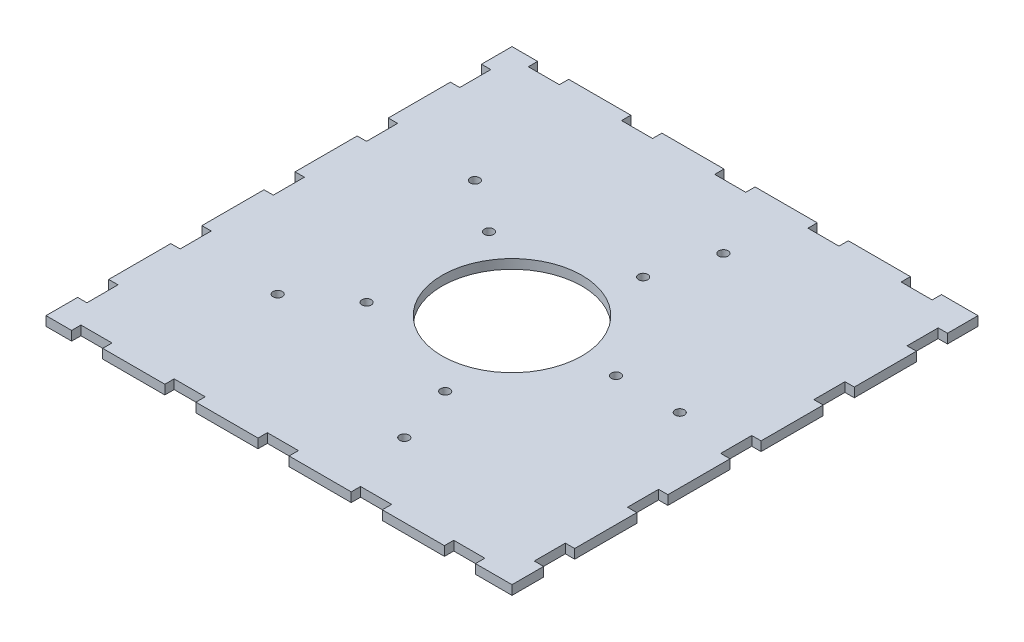
SolidWorks part; units mm, degrees
ref_plane "Front Plane" through (0, 0, 0) normal (0, 0, 1) x (1, 0, 0)
ref_plane "Top Plane" through (0, 0, 0) normal (0, 1, 0) x (1, 0, 0)
ref_plane "Right Plane" through (0, 0, 0) normal (1, 0, 0) x (0, 0, -1)
sketch "Sketch1" plane through (0, 0, 0) normal (0, 1, 0) x (-1, 0, 0)
  line L0 (75, -75) -> (-75, -75)
  line L1 (-75, -75) -> (-75, 75)
  line L2 (-75, 75) -> (75, 75)
  line L3 (75, 75) -> (75, -75)
  dimension "D1" = 150
  dimension "D2" = 150
extrude "Boss-Extrude1" add sketch "Sketch1" along normal blind 3 contours L0 L1 L2 L3
sketch "Sketch2" plane through (0, 3, 0) normal (0, 1, 0) x (1, 0, 0)
  circle A0 centre (0, 0) radius 22.5
  dimension "D1" = 45
extrude "Cut-Extrude1" cut sketch "Sketch2" against normal blind 3
sketch "Sketch3" plane through (0, 3, 0) normal (0, 1, 0) x (1, 0, 0)
  line L0 (-66.75, 75) -> (-66.75, 72)
  line L1 (-75, 75) -> (75, 75) construction
  line L2 (-66.75, 72) -> (-56.75, 72)
  line L3 (-56.75, 72) -> (-56.75, 75)
  line L4 (-56.75, 75) -> (-66.75, 75)
  line L5 (-75, 0) -> (75, 0) construction
  line L6 (-75, -75) -> (-75, 75) construction
  line L7 (75, 75) -> (75, -75) construction
  line L8 (-56.75, -75) -> (-66.75, -75)
  line L9 (-56.75, -72) -> (-56.75, -75)
  line L10 (-66.75, -72) -> (-56.75, -72)
  line L11 (-66.75, -75) -> (-66.75, -72)
  dimension "D1" = 10
  dimension "D2" = 3
extrude "Cut-Extrude2" cut sketch "Sketch3" against normal blind 3
pattern_linear "LPattern1" count 5 spacing 30 along (1, 0, 0) of "Cut-Extrude2"
sketch "Sketch4" plane through (0, 3, 0) normal (0, 1, 0) x (1, 0, 0)
  line L0 (-75, -64.8253) -> (-72, -64.8253)
  line L1 (-75, -75) -> (-75, 75) construction
  line L2 (-72, -64.8253) -> (-72, -54.8253)
  line L3 (-72, -54.8253) -> (-75, -54.8253)
  line L4 (-75, -54.8253) -> (-75, -64.8253)
  line L5 (0, 72) -> (0, -72) construction
  line L6 (-6.75, 72) -> (3.25, 72) construction
  line L7 (3.25, -72) -> (-6.75, -72) construction
  line L8 (75, -54.8253) -> (75, -64.8253)
  line L9 (72, -54.8253) -> (75, -54.8253)
  line L10 (72, -64.8253) -> (72, -54.8253)
  line L11 (75, -64.8253) -> (72, -64.8253)
  dimension "D1" = 10
  dimension "D2" = 3
extrude "Cut-Extrude3" cut sketch "Sketch4" against normal blind 3
pattern_linear "LPattern2" count 5 spacing 30 along (0, 0, -1) of "Cut-Extrude3"
sketch "Sketch5" plane through (0, 0, 0) normal (0, -1, 0) x (-1, 0, 0)
  circle A12 centre (0, 0) radius 54
  circle A13 centre (0, 0) radius 33.5
  circle A14 centre (-33.5, 0) radius 1.5
  circle A15 centre (-10.3521, 31.8604) radius 1.5
  circle A16 centre (27.1021, 19.6908) radius 1.5
  circle A17 centre (27.1021, -19.6908) radius 1.5
  circle A18 centre (-10.3521, -31.8604) radius 1.5
  circle A19 centre (-54, 0) radius 1.5
  circle A20 centre (-16.6869, 51.3571) radius 1.5
  circle A21 centre (43.6869, 31.7404) radius 1.5
  circle A22 centre (43.6869, -31.7404) radius 1.5
  circle A23 centre (-16.6869, -51.3571) radius 1.5
  point P15 (0, 0)
  point P16 (0, 0)
  point P18 (0, 0)
  point P27 (0, 0)
  point P28 (0, 0)
  dimension "D1" = 3
  dimension "D2" = 5
  dimension "D3" = 5
extrude "Cut-Extrude4" cut sketch "Sketch5" against normal blind 10 contours A17 | A18 | A14 | A15 | A16 | A21 | A22 | A23 | A19 | A20
